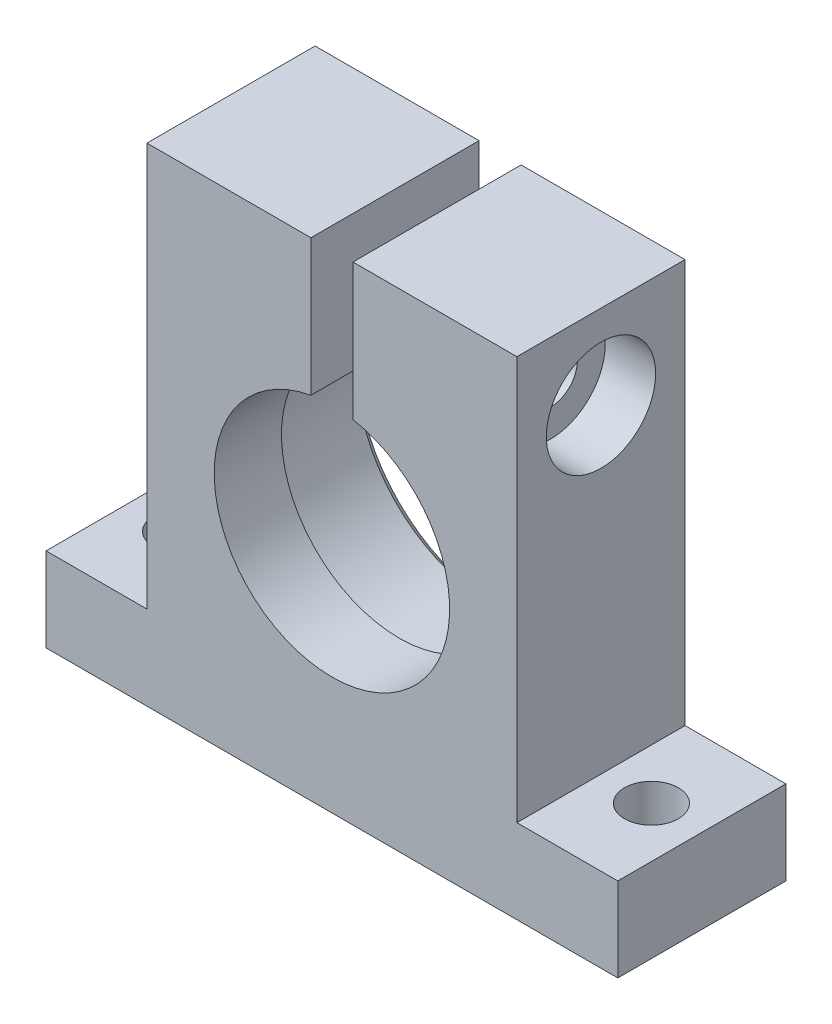
SolidWorks part; units mm, degrees
material "AISI 1045 Steel, cold drawn"
ref_plane "Front Plane" through (0, 0, 0) normal (0, 0, 1) x (1, 0, 0)
ref_plane "Top Plane" through (0, 0, 0) normal (0, 1, 0) x (1, 0, 0)
ref_plane "Right Plane" through (0, 0, 0) normal (1, 0, 0) x (0, 0, -1)
sketch "Sketch1" plane through (0, 0, 0) normal (0, 0, 1) x (1, 0, 0)
  line L1 (11, -14) -> (-11, -14)
  line L2 (11, -14) -> (11, 15)
  line L3 (11, 15) -> (-11, 15)
  line L4 (-11, -14) -> (-11, 15)
  line L5 (11, -14) -> (-11, 15) construction
  line L6 (11, 15) -> (-11, -14) construction
  circle A0 centre (0, 0) radius 8 construction
  point P3 (0, 0.5)
  dimension "D1" = 16
  dimension "D2" = 29
  dimension "D3" = 15
  dimension "D4" = 22
extrude "Boss-Extrude1" add sketch "Sketch1" along normal mid plane 10
sketch "Sketch3" plane through (0, -14, 0) normal (0, -1, 0) x (1, 0, 0)
  line L0 (-11, 5) -> (11, 5) construction
  line L1 (17, -5) -> (-17, -5)
  line L2 (17, -5) -> (17, 5)
  line L3 (17, 5) -> (-17, 5)
  line L4 (-17, -5) -> (-17, 5)
  line L5 (17, -5) -> (-17, 5) construction
  line L6 (17, 5) -> (-17, -5) construction
  point P0 (0, 0)
  dimension "D1" = 34
extrude "Boss-Extrude2" add sketch "Sketch3" against normal blind 5
hole_wizard "Ø16.0 (16) Diameter Hole1" positions "Sketch4" profile "Sketch5" hole size "Ø16.0" standard "ANSI Metric"
sketch "Sketch4" plane through (0, 0, -5) normal (0, 0, -1) x (-1, 0, 0)
  point P0 (0, 0)
sketch "Sketch5" plane through (0, 0, -5) normal (1, 0, 0) x (0, 1, 0)
  line L0 (0, 0) -> (0, 6)
  line L1 (0, 6) -> (8, 6)
  line L2 (8, 6) -> (8, 0)
  line L5 (8, 0) -> (0, 0)
  line L10 (0, 6) -> (-8, 6) construction
  line L11 (0, -6.35) -> (0, 107.95) construction
  dimension "Hole Dia." = 16
  dimension "Hole Depth" = 6
  dimension "Drill Angle" = 180
hole_wizard "Ø14.0 (14) Diameter Hole1" positions "Sketch13" profile "Sketch14" hole size "Ø14.0" standard "ANSI Metric" end condition through all
sketch "Sketch13" plane through (0, 0, 1) normal (0, 0, -1) x (-1, 0, 0)
  point P0 (0, 0)
sketch "Sketch14" plane through (0, 0, 1) normal (1, 0, 0) x (0, 1, 0)
  line L0 (0, 0) -> (0, 4)
  line L1 (0, 4) -> (7, 4)
  line L2 (7, 4) -> (7, 0)
  line L5 (7, 0) -> (0, 0)
  line L11 (0, -6.35) -> (0, 107.95) construction
  dimension "Thru Hole Dia." = 14
  dimension "Thru Hole Depth" = 4
hole_wizard "M3 Clearance Hole1" positions "Sketch6" profile "Sketch7" hole size "M3" standard "ANSI Metric" end condition through all
sketch "Sketch6" plane through (0, -9, 0) normal (0, 1, 0) x (1, 0, 0)
  line L0 (-17, -5) -> (-11, 5) construction
  line L2 (17, -5) -> (11, 5) construction
  point P0 (-14, 0)
  point P2 (14, 0)
sketch "Sketch7" plane through (-14, -9, 0) normal (1, 0, 0) x (0, 0, 1)
  line L0 (0, 0) -> (0, 5)
  line L1 (0, 5) -> (1.6, 5)
  line L2 (1.6, 5) -> (1.6, 0)
  line L5 (1.6, 0) -> (0, 0)
  line L11 (0, -6.35) -> (0, 107.95) construction
  dimension "Thru Hole Dia." = 3.2
  dimension "Thru Hole Depth" = 5
sketch "Sketch12" plane through (0, 0, 5) normal (0, 0, 1) x (1, 0, 0)
  line L0 (11, 15) -> (-11, 15) construction
  line L1 (1.25, 6.8875) -> (-1.25, 6.8875)
  line L2 (1.25, 6.8875) -> (1.25, 15)
  line L3 (1.25, 15) -> (-1.25, 15)
  line L4 (-1.25, 6.8875) -> (-1.25, 15)
  line L5 (1.25, 6.8875) -> (-1.25, 15) construction
  line L6 (1.25, 15) -> (-1.25, 6.8875) construction
  circle A1 centre (0, 0) radius 7 construction
  point P0 (0, 10.9437)
  dimension "D1" = 2.5
extrude "Cut-Extrude1" cut sketch "Sketch12" against normal through all
hole_wizard "M3x0.5 Tapped Hole1" positions "Sketch8" profile "Sketch9" tap size "M3x0.5" standard "ANSI Metric"
sketch "Sketch8" plane through (-11, 0, 0) normal (-1, 0, 0) x (0, 0, 1)
  line L0 (5, 15) -> (-5, 15) construction
  point P0 (0, 10)
  dimension "D1" = 5
cosmetic thread "Hole Thread2" parameters "D2"=3
sketch "Sketch9" plane through (-11, 10, 0) normal (0, 1, 0) x (0, 0, 1)
  line L0 (0, 0) -> (0, 9.75)
  line L1 (0, 9.75) -> (1.25, 9.75)
  line L2 (1.25, 9.75) -> (1.25, 0)
  line L5 (1.25, 0) -> (0, 0)
  line L11 (0, -6.35) -> (0, 107.95) construction
  dimension "Thru Tap Drill Dia." = 2.5
  dimension "Thru Tap Drill Depth" = 9.75
hole_wizard "CBORE for M3 SHCS1" positions "Sketch10" profile "Sketch11" counterbore size "M3" standard "ANSI Metric"
sketch "Sketch10" plane through (11, 0, 0) normal (1, 0, 0) x (0, 0, -1)
  point P0 (0, 10)
sketch "Sketch11" plane through (11, 10, 0) normal (0, 1, 0) x (0, 0, -1)
  line L0 (0, 0) -> (0, 9.75)
  line L1 (0, 9.75) -> (1.6, 9.75)
  line L3 (1.6, 9.75) -> (1.6, 3)
  line L4 (1.6, 3) -> (3.25, 3)
  line L5 (3.25, 3) -> (3.25, 0)
  line L7 (3.25, 0) -> (0, 0)
  line L11 (0, -6.35) -> (0, 107.95) construction
  dimension "Thru Hole Dia." = 3.2
  dimension "Thru Hole Depth" = 9.75
  dimension "C'Bore Dia." = 6.5
  dimension "C'Bore Depth" = 3
chamfer "Chamfer1" distance 0.5 angle 45 1 edges at (0, -8, -5)
